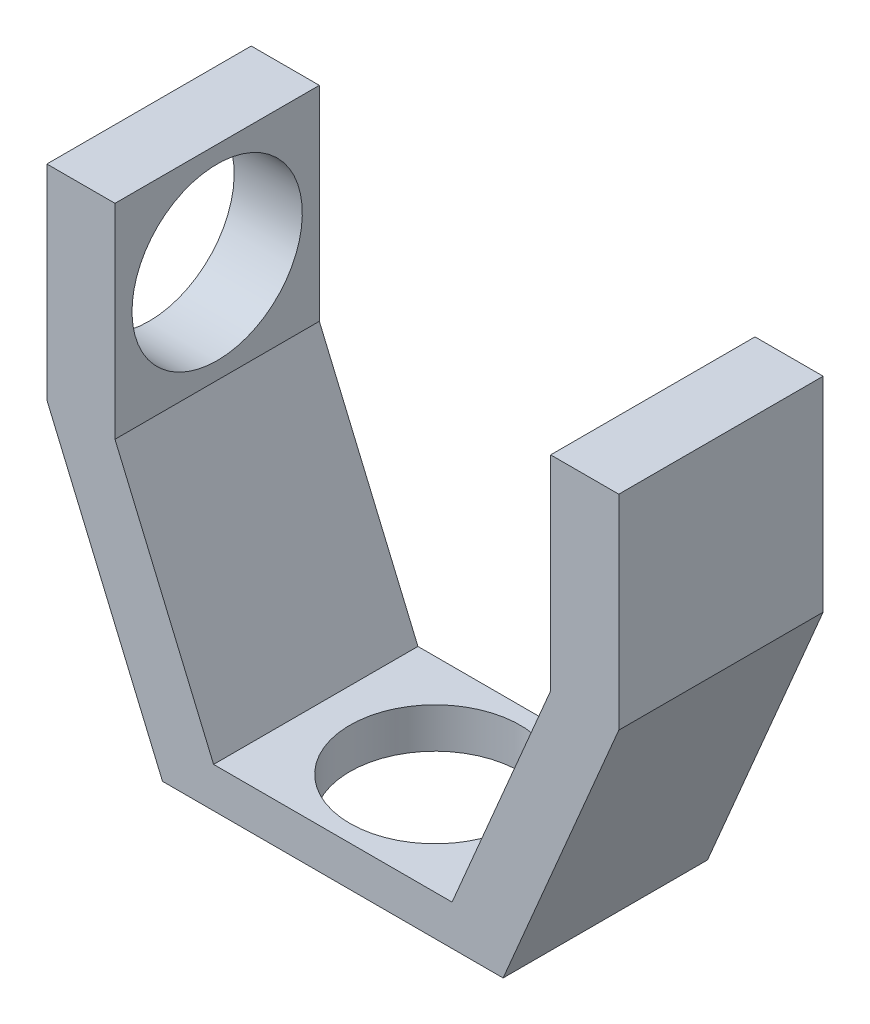
SolidWorks part; units mm, degrees
ref_plane "前视基准面" through (0, 0, 0) normal (0, 0, 1) x (1, 0, 0)
ref_plane "上视基准面" through (0, 0, 0) normal (0, 1, 0) x (1, 0, 0)
ref_plane "右视基准面" through (0, 0, 0) normal (1, 0, 0) x (0, 0, -1)
sketch "草图1" plane through (0, 0, 0) normal (0, 0, 1) x (1, 0, 0)
  line L0 (-161.7841, 76.9673) -> (-161.7841, 16.9673)
  line L1 (-161.7841, 16.9673) -> (-127.8261, -63.0327)
  line L2 (-127.8261, -63.0327) -> (-27.8261, -63.0327)
  line L3 (-27.8261, -63.0327) -> (6.1319, 16.9673)
  line L4 (6.1319, 16.9673) -> (6.1319, 76.9673)
  line L5 (6.1319, 76.9673) -> (-161.7841, 76.9673)
  dimension "D1" = 60
  dimension "D2" = 80
  dimension "D3" = 100
  dimension "D4" = 80
  dimension "D5" = 113
  dimension "D6" = 113
extrude "凸台-拉伸2" add sketch "草图1" along normal blind 60 contours L5 L0 L1 L2 L3 L4
sketch "草图5" plane through (0, 0, 60) normal (0, 0, 1) x (1, 0, 0)
  line L0 (-141.7841, 76.9673) -> (-141.7841, 16.9673)
  line L1 (6.1319, 76.9673) -> (-161.7841, 76.9673) construction
  line L2 (-13.8681, 76.9673) -> (-13.8681, 16.9673)
  line L3 (-141.7841, 16.9673) -> (-112.8364, -51.2291)
  line L4 (-112.8364, -51.2291) -> (-42.8158, -51.2291)
  line L5 (-42.8158, -51.2291) -> (-13.8681, 16.9673)
  line L6 (-141.7841, 76.9673) -> (-13.8681, 76.9673)
  dimension "D1" = 60
  dimension "D2" = 60
  dimension "D3" = 20
  dimension "D4" = 20
  dimension "D5" = 113
  dimension "D6" = 113
extrude "切除-拉伸2" cut sketch "草图5" against normal through all
sketch "草图7" plane through (-161.7841, 0, 0) normal (-1, 0, 0) x (0, 0, 1)
  line L0 (60, 76.9673) -> (0, 76.9673) construction
  line L1 (60, 76.9673) -> (60, 16.9673) construction
  circle A0 centre (30, 46.9673) radius 25
  point P2 (0, 0)
  point P5 (30, 76.9673)
  dimension "D1" = 30
  dimension "D2" = 30
extrude "切除-拉伸4" cut sketch "草图7" against normal blind 20
sketch "草图8" plane through (0, -51.2291, 0) normal (0, 1, 0) x (1, 0, 0)
  line L0 (-112.8364, 0) -> (-42.8158, 0) construction
  line L1 (-42.8158, 0) -> (-42.8158, -60) construction
  circle A0 centre (-77.8158, -30) radius 25
  dimension "D1" = 30
  dimension "D2" = 35
extrude "切除-拉伸5" cut sketch "草图8" against normal blind 20
